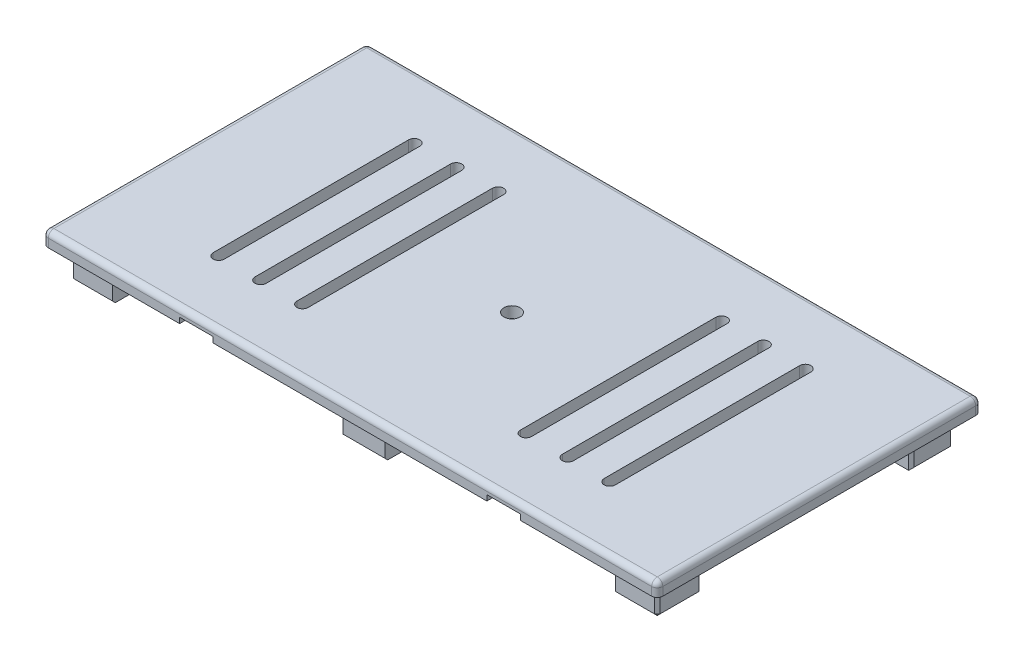
SolidWorks part; units mm, degrees
ref_plane "Front Plane" through (0, 0, 0) normal (0, 0, 1) x (1, 0, 0)
ref_plane "Top Plane" through (0, 0, 0) normal (0, 1, 0) x (1, 0, 0)
ref_plane "Right Plane" through (0, 0, 0) normal (1, 0, 0) x (0, 0, -1)
sketch "Sketch1" plane through (0, 0, 0) normal (0, 1, 0) x (1, 0, 0)
  line L1 (0, 0) -> (110, 0)
  line L2 (0, 0) -> (0, 58)
  line L3 (0, 58) -> (110, 58)
  line L4 (110, 0) -> (110, 58)
  dimension "D1" = 110
  dimension "D2" = 58
extrude "Boss-Extrude1" add sketch "Sketch1" along normal blind 2.5
sketch "Sketch2" plane through (0, 0, 0) normal (0, -1, 0) x (1, 0, 0)
  line L0 (0, -58) -> (0, 0) construction
  line L1 (2.5, -55.5) -> (107.5, -55.5)
  line L2 (2.5, -55.5) -> (2.5, -2.5)
  line L3 (2.5, -2.5) -> (107.5, -2.5)
  line L4 (107.5, -55.5) -> (107.5, -2.5)
  line L5 (0, 0) -> (110, 0) construction
  line L6 (110, 0) -> (110, -58) construction
  line L7 (110, -58) -> (0, -58) construction
  dimension "D1" = 2.5
  dimension "D2" = 2.5
  dimension "D3" = 2.5
  dimension "D4" = 2.5
  dimension "D5" = 53
  dimension "D6" = 105
extrude "Boss-Extrude2" add sketch "Sketch2" along normal blind 1.5
sketch "Sketch3" plane through (0, -1.5, 0) normal (0, -1, 0) x (1, 0, 0)
  line L0 (55, -5.5) -> (55, -55.5) construction
  line L1 (2.5, -55.5) -> (107.5, -55.5) construction
  line L2 (2.5, -55.5) -> (107.5, -55.5) construction
  line L3 (107.5, -29) -> (2.5, -29) construction
  line L4 (107.5, -55.5) -> (107.5, -2.5) construction
  line L5 (2.5, -2.5) -> (2.5, -55.5) construction
  line L6 (58.75, -2.5) -> (58.75, -5.5)
  line L7 (2.5, -2.5) -> (10, -2.5)
  line L8 (2.5, -2.5) -> (2.5, -10)
  line L9 (2.5, -10) -> (5.5, -10)
  line L10 (10, -2.5) -> (10, -5.5)
  line L13 (10, -5.5) -> (5.5, -5.5)
  line L14 (5.5, -10) -> (5.5, -5.5)
  line L15 (58.75, -2.5) -> (51.25, -2.5)
  line L17 (58.75, -5.5) -> (51.25, -5.5)
  line L18 (51.25, -2.5) -> (51.25, -5.5)
  line L19 (107.5, -2.5) -> (107.5, -10)
  line L20 (107.5, -10) -> (104.5, -10)
  line L21 (104.5, -10) -> (104.5, -5.5)
  line L22 (100, -5.5) -> (104.5, -5.5)
  line L23 (100, -2.5) -> (100, -5.5)
  line L24 (107.5, -2.5) -> (100, -2.5)
  line L25 (107.5, -55.5) -> (100, -55.5)
  line L26 (100, -55.5) -> (100, -52.5)
  line L27 (100, -52.5) -> (104.5, -52.5)
  line L28 (104.5, -48) -> (104.5, -52.5)
  line L29 (107.5, -48) -> (104.5, -48)
  line L30 (107.5, -55.5) -> (107.5, -48)
  line L31 (58.75, -55.5) -> (58.75, -52.5)
  line L32 (58.75, -55.5) -> (51.25, -55.5)
  line L33 (51.25, -55.5) -> (51.25, -52.5)
  line L34 (58.75, -52.5) -> (51.25, -52.5)
  line L35 (2.5, -55.5) -> (2.5, -48)
  line L36 (2.5, -48) -> (5.5, -48)
  line L37 (5.5, -48) -> (5.5, -52.5)
  line L38 (10, -52.5) -> (5.5, -52.5)
  line L39 (10, -55.5) -> (10, -52.5)
  line L40 (2.5, -55.5) -> (10, -55.5)
  dimension "D1" = 7.5
  dimension "D2" = 7.5
  dimension "D3" = 3
  dimension "D4" = 3
  dimension "D5" = 7.5
  dimension "D6" = 3
extrude "Boss-Extrude3" add sketch "Sketch3" along normal blind 4
fillet "Fillet1" radius 1 4 edges at (5.5, -3.5, -52.5) (104.5, -3.5, -52.5) (104.5, -3.5, -5.5) (5.5, -3.5, -5.5)
sketch "Sketch4" plane through (0, 0, 0) normal (0, -1, 0) x (1, 0, 0)
  line L0 (55, 0) -> (55, -58) construction
  line L1 (0, 0) -> (110, 0) construction
  line L2 (110, -58) -> (0, -58) construction
  line L3 (0, -29) -> (55, -29) construction
  line L4 (0, -58) -> (0, 0) construction
  line L6 (27.5, -29) -> (27.5, -2.5) construction
  line L7 (107.5, -2.5) -> (2.5, -2.5) construction
  line L8 (30.5, 0) -> (24.5, 0)
  line L10 (30.5, -2.5) -> (24.5, -2.5)
  line L11 (24.5, 0) -> (24.5, -2.5)
  line L12 (30.5, 0) -> (30.5, -2.5)
  line L13 (79.5, 0) -> (79.5, -2.5)
  line L14 (79.5, 0) -> (85.5, 0)
  line L15 (85.5, 0) -> (85.5, -2.5)
  line L16 (79.5, -2.5) -> (85.5, -2.5)
  line L17 (79.5, -58) -> (85.5, -58)
  line L18 (85.5, -58) -> (85.5, -55.5)
  line L19 (79.5, -55.5) -> (85.5, -55.5)
  line L20 (79.5, -58) -> (79.5, -55.5)
  line L21 (30.5, -58) -> (30.5, -55.5)
  line L22 (30.5, -58) -> (24.5, -58)
  line L23 (24.5, -58) -> (24.5, -55.5)
  line L24 (30.5, -55.5) -> (24.5, -55.5)
extrude "Cut-Extrude1" cut sketch "Sketch4" against normal blind 1
fillet "Fillet2" radius 1 4 edges at (0, 1.25, -58) (0, 1.25, 0) (110, 1.25, -58) (110, 1.25, 0)
chamfer "Chamfer1" distance 0.5 angle 45 18 edges at (55, -5.5, -55.5) (2.5, -3.5, -48) (2.5, -2.75, -55.5) (10, -3.5, -55.5) (107.5, -3.5, -48) (100, -3.5, -55.5) (107.5, -2.75, -55.5) (107.5, -2.75, -2.5) (107.5, -5.5, -6.25) (103.75, -5.5, -2.5) (55, -5.5, -2.5) (2.5, -5.5, -6.25) (6.25, -5.5, -2.5) (2.5, -2.75, -2.5) (2.5, -5.5, -51.75) (6.25, -5.5, -55.5) (103.75, -5.5, -55.5) (107.5, -5.5, -51.75)
sketch "Sketch5" plane through (0, 2.5, 0) normal (0, 1, 0) x (1, 0, 0)
  line L0 (0, 29) -> (55, 29) construction
  line L1 (0, 57) -> (0, 1) construction
  line L3 (55, 58) -> (55, 0) construction
  line L4 (109, 58) -> (1, 58) construction
  line L5 (1, 0) -> (109, 0) construction
  line L6 (27.5, 29) -> (27.5, 46.5) construction
  line L11 (27.5, 29) -> (27.5, 11.5) construction
  line L14 (27.5, 46.5) -> (27.5, 11.5) construction
  line L17 (28.5, 46.5) -> (28.5, 11.5)
  line L20 (26.5, 46.5) -> (26.5, 11.5)
  line L23 (34, 46.5) -> (34, 11.5)
  line L26 (36, 46.5) -> (36, 11.5)
  line L27 (35, 46.5) -> (35, 11.5) construction
  line L28 (20, 46.5) -> (20, 11.5) construction
  line L29 (21, 46.5) -> (21, 11.5)
  line L30 (19, 46.5) -> (19, 11.5)
  line L31 (90, 46.5) -> (90, 11.5) construction
  line L32 (89, 46.5) -> (89, 11.5)
  line L33 (91, 46.5) -> (91, 11.5)
  line L34 (75, 46.5) -> (75, 11.5) construction
  line L35 (74, 46.5) -> (74, 11.5)
  line L36 (76, 46.5) -> (76, 11.5)
  line L37 (82.5, 46.5) -> (82.5, 11.5) construction
  line L38 (81.5, 46.5) -> (81.5, 11.5)
  line L39 (83.5, 46.5) -> (83.5, 11.5)
  arc A14 (28.5, 46.5) -> (26.5, 46.5) centre (27.5, 46.5) ccw
  arc A15 (26.5, 11.5) -> (28.5, 11.5) centre (27.5, 11.5) ccw
  arc A16 (36, 46.5) -> (34, 46.5) centre (35, 46.5) ccw
  arc A17 (34, 11.5) -> (36, 11.5) centre (35, 11.5) ccw
  arc A18 (21, 46.5) -> (19, 46.5) centre (20, 46.5) ccw
  arc A19 (19, 11.5) -> (21, 11.5) centre (20, 11.5) ccw
  arc A20 (89, 46.5) -> (91, 46.5) centre (90, 46.5) cw
  arc A21 (91, 11.5) -> (89, 11.5) centre (90, 11.5) cw
  arc A22 (74, 46.5) -> (76, 46.5) centre (75, 46.5) cw
  arc A23 (76, 11.5) -> (74, 11.5) centre (75, 11.5) cw
  arc A24 (81.5, 46.5) -> (83.5, 46.5) centre (82.5, 46.5) cw
  arc A25 (83.5, 11.5) -> (81.5, 11.5) centre (82.5, 11.5) cw
  point P5 (27.5, 29)
  point P21 (35, 29)
  point P27 (20, 29)
  point P34 (90, 29)
  point P41 (75, 29)
  point P48 (82.5, 29)
  dimension "D3" = 1
  dimension "D1" = 17.5
  dimension "D2" = 17.5
  dimension "D4" = 2
  dimension "D5" = 2
extrude "Cut-Extrude2" cut sketch "Sketch5" against normal through all
fillet "Fillet3" radius 1 8 edges at (0.2929, 2.5, -0.2929) (0, 2.5, -29) (0.2929, 2.5, -57.7071) (55, 2.5, -58) (109.7071, 2.5, -57.7071) (110, 2.5, -29) (109.7071, 2.5, -0.2929) (55, 2.5, 0)
sketch "Sketch6" plane through (0, 2.5, 0) normal (0, 1, 0) x (1, 0, 0)
  line L0 (55, 58) -> (55, 0) construction
  line L1 (1, 58) -> (109, 58) construction
  line L2 (109, 0) -> (1, 0) construction
  circle A0 centre (55, 29) radius 1.45
  dimension "D1" = 2.9
extrude "Cut-Extrude3" cut sketch "Sketch6" against normal through all
sketch "Sketch7" plane through (0, -1.5, 0) normal (0, -1, 0) x (1, 0, 0)
  circle A0 centre (55, -29) radius 1.675
  dimension "D1" = 3.35
extrude "Cut-Extrude4" cut sketch "Sketch7" against normal blind 2
